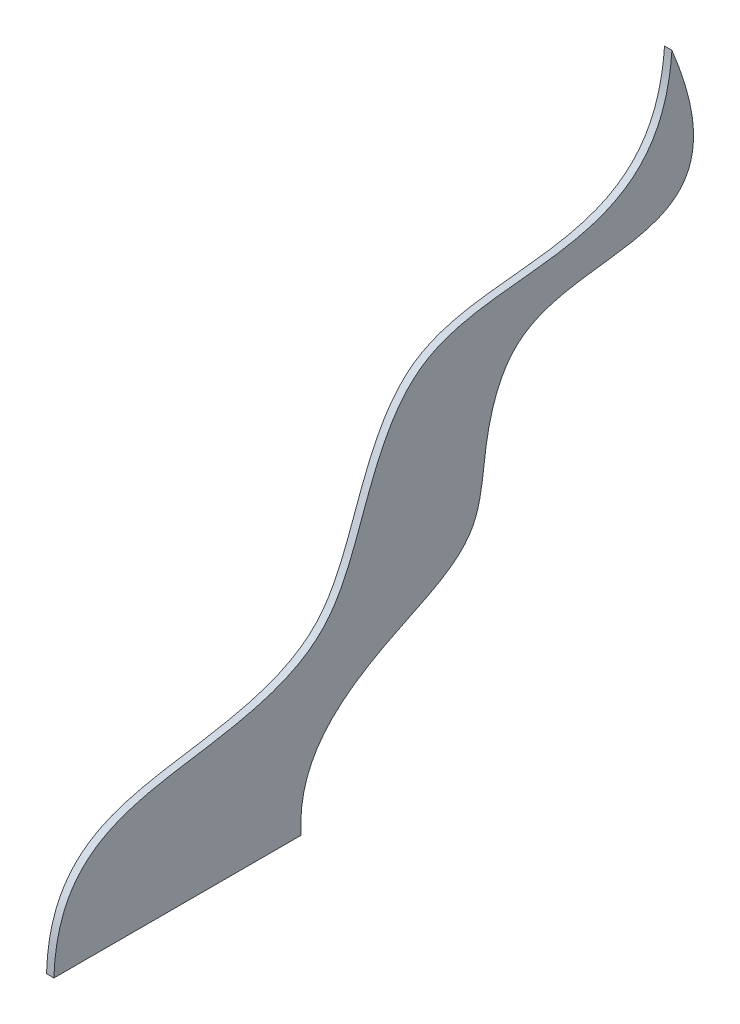
SolidWorks part; units mm, degrees
ref_plane "Front" through (0, 0, 0) normal (0, 0, 1) x (1, 0, 0)
ref_plane "Top" through (0, 0, 0) normal (0, 1, 0) x (1, 0, 0)
ref_plane "Right" through (0, 0, 0) normal (1, 0, 0) x (0, 0, -1)
sketch "Sketch2" plane through (0, 0, 0) normal (1, 0, 0) x (0, 0, -1)
  line L0 (0, 0) -> (100, 0)
  line L2 (100, 0) -> (250, 200) construction
  line L3 (125, 100) -> (0, 0) construction
  line L4 (125, 100) -> (250, 200) construction
  spline S0 degree 1 poles (0, 0) (62.5, 50) knots 0 0 1 1
  spline S1 degree 3 poles (0, 0) (1.2966, 42.8672) (48.3958, 46.0264) (110.8686, 59.5684) (125.7299, 102.9027) (152.8785, 172.253) (245.4014, 132.791) (250, 200) knots 0 0 0 0 0.258214 0.403782 0.510036 0.643754 1 1 1 1
  spline S2 degree 3 poles (100, 0) (98.1148, 27.9437) (126.6688, 48.2589) (173.094, 67.0114) (173.4899, 101.0648) (193.3341, 160.4532) (283.1993, 119.3215) (250, 200) knots 0 0 0 0 0.251772 0.382046 0.484861 0.597251 1 1 1 1
  point P3 (50, 0)
  point P5 (62.5, 50)
  point P6 (187.5, 150)
  point P8 (125, 100)
  point P11 (175, 100)
  point P13 (139.2354, 52.3139)
  point P15 (212.5, 150)
  dimension "D1" = 100
  dimension "D2" = 200
  dimension "D3" = 200
extrude "Boss-Extrude1" add sketch "Sketch2" along normal blind 3 contours L0 S2 S1
